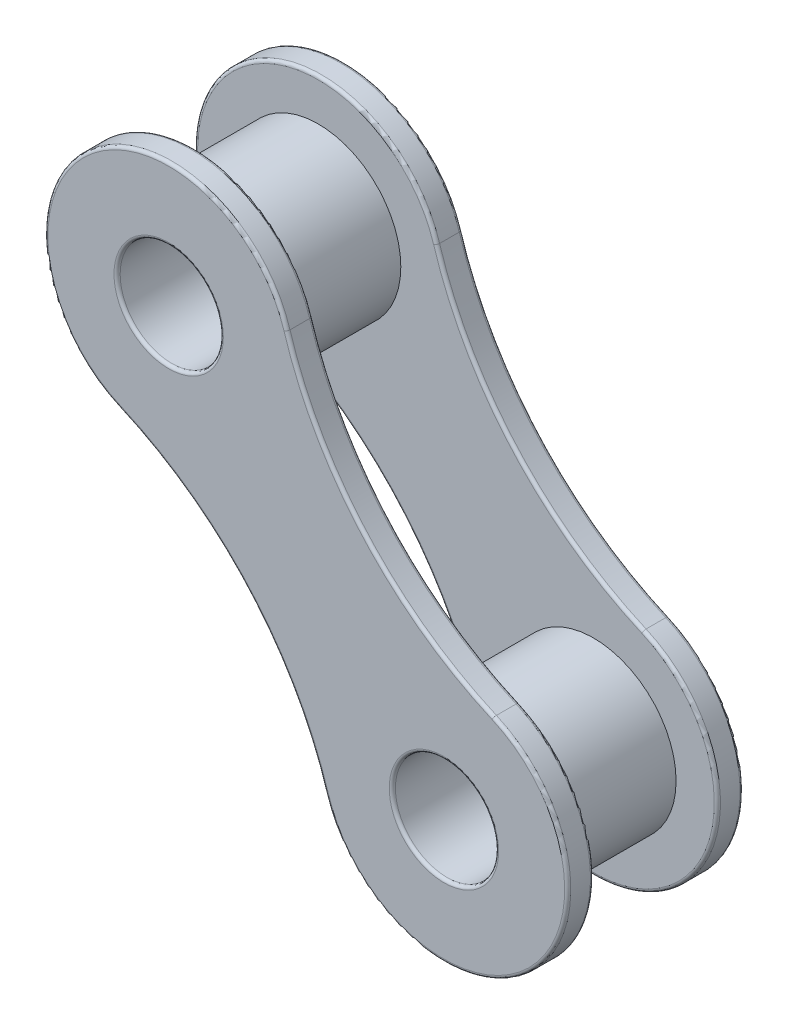
SolidWorks part; units mm, degrees
material "AISI 1020"
ref_plane "Спереди" through (0, 0, 0) normal (0, 0, 1) x (1, 0, 0)
ref_plane "Сверху" through (0, 0, 0) normal (0, 1, 0) x (1, 0, 0)
ref_plane "Справа" through (0, 0, 0) normal (1, 0, 0) x (0, 0, -1)
sketch "Эскиз1" plane through (0, 0, 0) normal (0, 0, 1) x (1, 0, 0)
  line L0 (197.7015, 38.1053) -> (11.6171, 69.2998)
  line L1 (197.7015, -38.1053) -> (11.6171, -69.2998)
  line L3 (46.8644, -52.3559) -> (59.7165, -37.0319)
  line L4 (59.7165, -37.0319) -> (67.7306, -18.7078)
  line L5 (67.7306, -18.7078) -> (70.2576, 1.132)
  line L6 (70.2576, 1.132) -> (67.0928, 20.88)
  line L7 (67.0928, 20.88) -> (58.4925, 38.9364)
  line L8 (58.4925, 38.9364) -> (45.1535, 53.8384)
  line L9 (45.1535, 53.8384) -> (28.1564, 64.3788)
  line L10 (28.1564, 64.3788) -> (8.8783, 69.7036)
  line L11 (8.8783, 69.7036) -> (-11.1191, 69.3814)
  line L12 (-11.1191, 69.3814) -> (-30.2157, 63.4383)
  line L13 (-30.2157, 63.4383) -> (-46.8644, 52.3559)
  line L14 (-46.8644, 52.3559) -> (-59.7165, 37.0319)
  line L15 (-59.7165, 37.0319) -> (-67.7306, 18.7078)
  line L16 (-67.7306, 18.7078) -> (-70.2576, -1.132)
  line L17 (-70.2576, -1.132) -> (-67.0928, -20.88)
  line L18 (-67.0928, -20.88) -> (-58.4925, -38.9364)
  line L19 (-58.4925, -38.9364) -> (-45.1535, -53.8384)
  line L20 (-45.1535, -53.8384) -> (-28.1564, -64.3788)
  line L21 (-28.1564, -64.3788) -> (-8.8783, -69.7036)
  line L22 (-8.8783, -69.7036) -> (11.1191, -69.3814)
  line L23 (11.1191, -69.3814) -> (30.2157, -63.4383)
  line L24 (30.2157, -63.4383) -> (46.8644, -52.3559)
  line L25 (154.7463, -12.4759) -> (165.8834, -29.0881)
  line L26 (165.8834, -29.0881) -> (183.8345, -37.9062)
  line L27 (183.8345, -37.9062) -> (203.7896, -36.5674)
  line L28 (203.7896, -36.5674) -> (220.4018, -25.4303)
  line L29 (220.4018, -25.4303) -> (229.2199, -7.4792)
  line L30 (229.2199, -7.4792) -> (227.8811, 12.4759)
  line L31 (227.8811, 12.4759) -> (216.744, 29.0881)
  line L32 (216.744, 29.0881) -> (198.7929, 37.9062)
  line L33 (198.7929, 37.9062) -> (178.8378, 36.5674)
  line L34 (178.8378, 36.5674) -> (162.2256, 25.4303)
  line L35 (162.2256, 25.4303) -> (153.4075, 7.4792)
  line L36 (153.4075, 7.4792) -> (154.7463, -12.4759)
  arc A0 (11.6171, 69.2998) -> (11.6171, -69.2998) centre (0, 0) ccw
  arc A1 (197.7015, 38.1053) -> (197.7015, -38.1053) centre (191.3137, 0) cw
  circle A2 centre (0, 0) radius 69.5515 construction
  circle A3 centre (191.3137, 0) radius 37.3205 construction
  dimension "D1" = 730
  dimension "D2" = 20
  dimension "D3" = 20
sketch "Эскиз2" plane through (0, 0, 0) normal (0, 0, 1) x (1, 0, 0)
  line L0 (197.7015, 38.1053) -> (11.6171, 69.2998) construction
  line L1 (197.7015, 38.1053) -> (11.6171, 69.2998)
  line L2 (197.7015, -38.1053) -> (11.6171, -69.2998) construction
  line L3 (197.7015, -38.1053) -> (11.6171, -69.2998)
  arc A0 (11.6171, 69.2998) -> (11.6171, -69.2998) centre (0, 0) ccw construction
  arc A1 (11.6171, 69.2998) -> (11.6171, -69.2998) centre (0, 0) ccw
  arc A2 (197.7015, -38.1053) -> (197.7015, 38.1053) centre (191.3137, 0) ccw construction
  arc A3 (197.7015, -38.1053) -> (197.7015, 38.1053) centre (191.3137, 0) ccw
sketch "Эскиз3" plane through (0, 0, 0) normal (0, 0, 1) x (1, 0, 0)
  line L0 (58.4925, 38.9364) -> (45.1535, 53.8384) construction
  circle A2 centre (45.1535, 53.8384) radius 2.5
  circle A3 centre (58.4925, 38.9364) radius 2.5
  circle A4 centre (45.1535, 53.8384) radius 6
  circle A5 centre (58.4925, 38.9364) radius 6
  arc A6 (42.7568, 48.3379) -> (52.7611, 37.1614) centre (35.5668, 31.8363) cw
  arc A7 (50.8849, 55.6135) -> (60.8892, 44.4369) centre (68.0792, 60.9386) ccw
  dimension "D1" = 5
  dimension "D2" = 12
  dimension "D3" = 18
sketch "Эскиз4" plane through (0, 0, 0) normal (0, 0, 1) x (1, 0, 0)
  circle A0 centre (45.1535, 53.8384) radius 2.5 construction
  circle A1 centre (45.1535, 53.8384) radius 2.5
  circle A2 centre (58.4925, 38.9364) radius 2.5 construction
  circle A3 centre (58.4925, 38.9364) radius 2.5
  circle A4 centre (45.1535, 53.8384) radius 4
  circle A5 centre (58.4925, 38.9364) radius 4
  dimension "D1" = 8
extrude "Бобышка-Вытянуть1" add sketch "Эскиз4" along normal mid plane 6
sketch "Эскиз5" plane through (0, 0, 3) normal (0, 0, 1) x (1, 0, 0)
  arc A0 (52.7611, 37.1614) -> (42.7568, 48.3379) centre (35.5668, 31.8363) ccw construction
  arc A1 (52.7611, 37.1614) -> (42.7568, 48.3379) centre (35.5668, 31.8363) ccw
  circle A2 centre (45.1535, 53.8384) radius 6 construction
  arc A3 (50.8849, 55.6135) -> (42.7568, 48.3379) centre (45.1535, 53.8384) ccw
  arc A4 (50.8849, 55.6135) -> (60.8892, 44.4369) centre (68.0792, 60.9386) ccw construction
  arc A5 (50.8849, 55.6135) -> (60.8892, 44.4369) centre (68.0792, 60.9386) ccw
  circle A6 centre (58.4925, 38.9364) radius 6 construction
  arc A7 (52.7611, 37.1614) -> (60.8892, 44.4369) centre (58.4925, 38.9364) ccw
  circle A8 centre (45.1535, 53.8384) radius 2.5 construction
  circle A9 centre (45.1535, 53.8384) radius 2.5
  circle A10 centre (58.4925, 38.9364) radius 2.5 construction
  circle A11 centre (58.4925, 38.9364) radius 2.5
extrude "Бобышка-Вытянуть2" add sketch "Эскиз5" along normal blind 1.25
mirror "Зеркальное отражение1" about plane through (0, 0, 0) normal (0, 0, 1) of "Бобышка-Вытянуть2"
fillet "Скругление1" radius 0.15 20 edges at (54.6674, 48.9335, -4.25) (62.4942, 34.4658, -4.25) (48.9786, 43.8414, -4.25) (54.6674, 48.9335, -3) (62.4942, 34.4658, -3) (48.9786, 43.8414, -3) (54.6674, 48.9335, 3) (62.4942, 34.4658, 3) (48.9786, 43.8414, 3) (54.6674, 48.9335, 4.25) (62.4942, 34.4658, 4.25) (48.9786, 43.8414, 4.25) (47.6535, 53.8384, -4.25) (60.9925, 38.9364, -4.25) (60.9925, 38.9364, 4.25) (41.1518, 58.3091, -4.25) (41.1518, 58.3091, -3) (47.6535, 53.8384, 4.25) (41.1518, 58.3091, 3) (41.1518, 58.3091, 4.25)
sketch "Эскиз6" plane through (0, 0, 0) normal (0, 0, 1) x (1, 0, 0)
  circle A3 centre (45.1535, 53.8384) radius 2.5 construction
  circle A5 centre (45.1535, 53.8384) radius 2.5
  circle A7 centre (58.4925, 38.9364) radius 2.5 construction
  circle A9 centre (58.4925, 38.9364) radius 2.5
